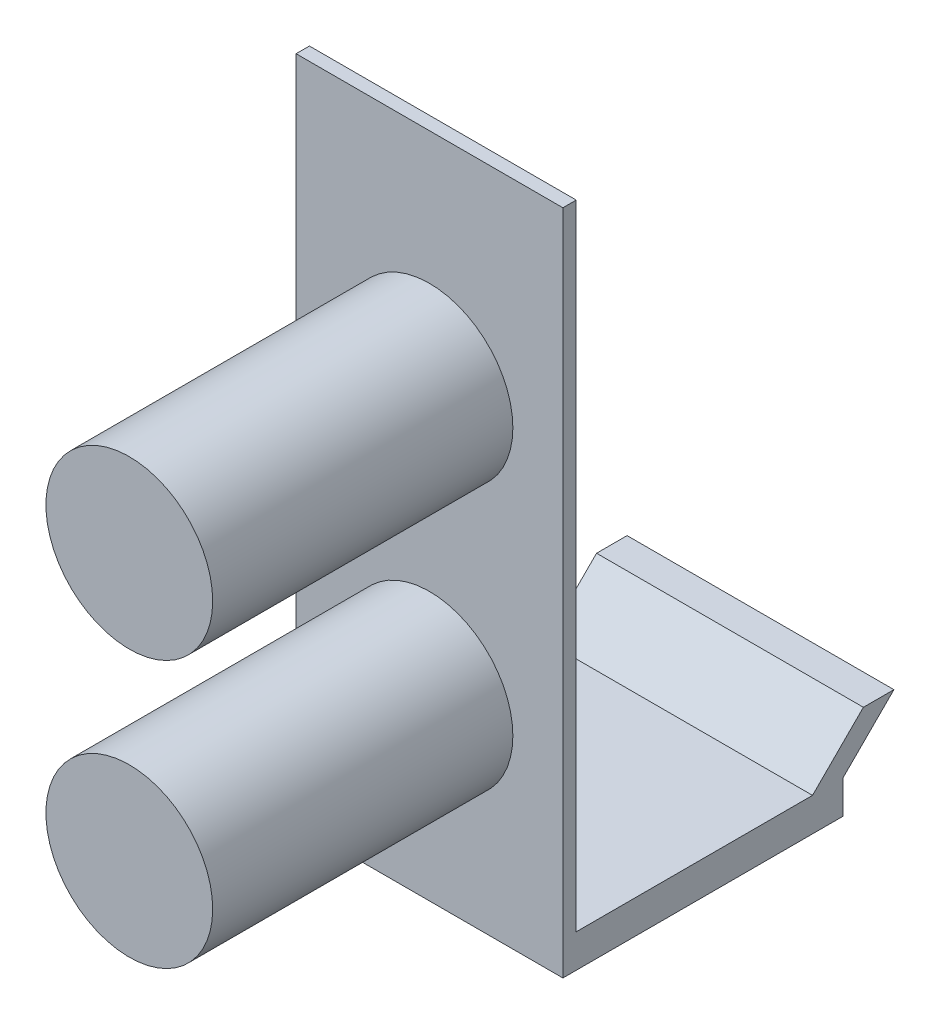
SolidWorks part; units mm, degrees
ref_plane "Front Plane" through (0, 0, 0) normal (0, 0, 1) x (1, 0, 0)
ref_plane "Top Plane" through (0, 0, 0) normal (0, 1, 0) x (1, 0, 0)
ref_plane "Right Plane" through (0, 0, 0) normal (1, 0, 0) x (0, 0, -1)
sketch "Sketch1" plane through (0, 0, 0) normal (0, 0, 1) x (1, 0, 0)
  line L1 (-25.4, 63.5) -> (25.4, 63.5)
  line L2 (-25.4, 63.5) -> (-25.4, -63.5)
  line L3 (-25.4, -63.5) -> (25.4, -63.5)
  line L4 (25.4, 63.5) -> (25.4, -63.5)
  line L5 (-25.4, 63.5) -> (25.4, -63.5) construction
  line L6 (-25.4, -63.5) -> (25.4, 63.5) construction
  point P0 (0, 0)
  dimension "D1" = 50.8
  dimension "D2" = 127
extrude "Boss-Extrude1" add sketch "Sketch1" along normal blind 2.54
sketch "Sketch2" plane through (0, 0, 2.54) normal (0, 0, 1) x (1, 0, 0)
  circle A0 centre (0, 22.4655) radius 15.875
  circle A1 centre (0, -28.3345) radius 15.875
  dimension "D1" = 31.75
  dimension "D2" = 31.75
  dimension "D3" = 19.05
extrude "Boss-Extrude2" add sketch "Sketch2" along normal blind 57.15
sketch "Sketch3" plane through (0, 0, 0) normal (0, 0, -1) x (-1, 0, 0)
  line L1 (-25.4, -57.15) -> (25.4, -57.15)
  line L2 (-25.4, -57.15) -> (-25.4, -63.5)
  line L3 (-25.4, -63.5) -> (25.4, -63.5)
  line L4 (25.4, -57.15) -> (25.4, -63.5)
  line L5 (-25.4, -57.15) -> (25.4, -63.5) construction
  line L6 (-25.4, -63.5) -> (25.4, -57.15) construction
  point P0 (0, -60.325)
  dimension "D1" = 6.35
extrude "Boss-Extrude3" add sketch "Sketch3" along normal blind 50.8
sketch "Sketch4" plane through (25.4, 0, 0) normal (1, 0, 0) x (0, 0, -1)
  line L0 (44.45, -63.5) -> (60.4821, -47.4679)
  line L1 (-2.54, -63.5) -> (50.8, -63.5) construction
  line L2 (50.8, -57.15) -> (50.8, -63.5) construction
  line L3 (38.6357, -63.5) -> (54.6678, -47.4679)
  line L4 (60.4821, -47.4679) -> (54.6678, -47.4679)
  line L5 (38.6357, -63.5) -> (44.45, -63.5)
  dimension "D1" = 45
extrude "Boss-Extrude4" add sketch "Sketch4" against normal up to surface (50.8 mm away) up to face at (-25.4, -19.05, -16.0867)
